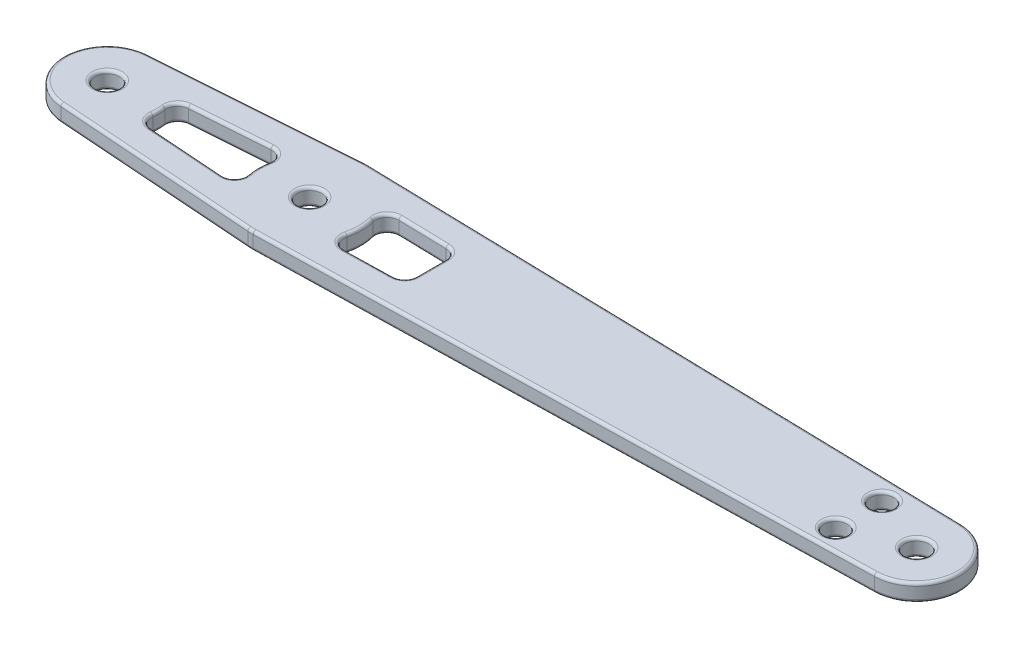
SolidWorks part; units mm, degrees
ref_plane "Front Plane" through (0, 0, 0) normal (0, 0, 1) x (1, 0, 0)
ref_plane "Top Plane" through (0, 0, 0) normal (0, 1, 0) x (1, 0, 0)
ref_plane "Right Plane" through (0, 0, 0) normal (1, 0, 0) x (0, 0, -1)
sketch "Sketch1" plane through (0, 0, 0) normal (0, 1, 0) x (1, 0, 0)
  line L0 (-0.5357, 7.4808) -> (34.2857, 9.9745)
  line L1 (-0.5357, -7.4808) -> (34.2857, -9.9745)
  line L2 (35.2381, 9.9972) -> (140.1786, 7.4979)
  line L3 (140.1786, -7.4979) -> (35.2381, -9.9972)
  circle A0 centre (0, 0) radius 2.1
  circle A1 centre (35, 0) radius 2.1
  circle A2 centre (140, 0) radius 2.1
  arc A3 (-0.5357, 7.4808) -> (-0.5357, -7.4808) centre (0, 0) ccw
  arc A4 (140.1786, -7.4979) -> (140.1786, 7.4979) centre (140, 0) ccw
  arc A5 (35.2381, 9.9972) -> (34.2857, 9.9745) centre (35, 0) ccw
  arc A6 (34.2857, -9.9745) -> (35.2381, -9.9972) centre (35, 0) ccw
  dimension "D1" = 4.2
  dimension "D2" = 4.2
  dimension "D4" = 4.2
  dimension "D6" = 15
  dimension "D7" = 15
  dimension "D8" = 20
  dimension "D3" = 35
  dimension "D5" = 140
extrude "Boss-Extrude1" add sketch "Sketch1" along normal blind 3
sketch "Sketch3" plane through (0, 0, 0) normal (0, -1, 0) x (1, 0, 0)
  line L2 (130.1755, 2.7347) -> (122.0476, 2.9283) construction
  line L3 (35.2381, 9.9972) -> (140.1786, 7.4979) construction
  line L4 (130.1755, -2.7347) -> (122.0476, -2.9283) construction
  line L5 (140.1786, -7.4979) -> (35.2381, -9.9972) construction
  line L6 (120, 0.9288) -> (120, -0.9288) construction
  line L8 (-0.1786, 2.4936) -> (34.6429, 4.9872)
  line L9 (10.782, 3.2785) -> (24.0869, 4.2313)
  line L11 (34.6429, -4.9872) -> (-0.1786, -2.4936)
  line L12 (24.0869, -4.2313) -> (10.782, -3.2785)
  line L22 (35.119, 4.9986) -> (140.0595, 2.4993)
  line L23 (45.6991, 4.7466) -> (54.0476, 4.5478)
  line L24 (56, 2.5483) -> (56, -2.5483)
  line L25 (140.0595, -2.4993) -> (35.119, -4.9986)
  line L26 (54.0476, -4.5478) -> (45.6991, -4.7466)
  arc A0 (26.188, 1.8298) -> (26.188, -1.8298) centre (35, 0) ccw
  arc A1 (8.9385, -1.0502) -> (8.9385, 1.0502) centre (0, 0) ccw
  arc A2 (8.9385, 1.0502) -> (10.782, 3.2785) centre (10.9248, 1.2836) cw
  arc A3 (8.9385, -1.0502) -> (10.782, -3.2785) centre (10.9248, -1.2836) ccw
  arc A4 (26.188, -1.8298) -> (24.0869, -4.2313) centre (24.2297, -2.2364) cw
  arc A5 (26.188, 1.8298) -> (24.0869, 4.2313) centre (24.2297, 2.2364) ccw
  arc A6 (43.7148, -2.2477) -> (43.7148, 2.2477) centre (35, 0) ccw
  circle A7 centre (35, 0) radius 2.1 construction
  arc A8 (43.7148, 2.2477) -> (45.6991, 4.7466) centre (45.6514, 2.7472) cw
  arc A9 (43.7148, -2.2477) -> (45.6991, -4.7466) centre (45.6514, -2.7472) ccw
  arc A10 (56, -2.5483) -> (54.0476, -4.5478) centre (54, -2.5483) cw
  arc A11 (56, 2.5483) -> (54.0476, 4.5478) centre (54, 2.5483) ccw
  arc A13 (131.1365, 1.5615) -> (131.1365, -1.5615) centre (140, 0) ccw construction
  arc A14 (130.1755, -2.7347) -> (131.1365, -1.5615) centre (130.1517, -1.735) ccw construction
  arc A15 (130.1755, 2.7347) -> (131.1365, 1.5615) centre (130.1517, 1.735) cw construction
  arc A16 (122.0476, -2.9283) -> (120, -0.9288) centre (122, -0.9288) cw construction
  arc A17 (122.0476, 2.9283) -> (120, 0.9288) centre (122, 0.9288) ccw construction
  point P55 (120, 0)
  dimension "D1" = 18
  dimension "D2" = 18
  dimension "D5" = 2
  dimension "D6" = 18
  dimension "D10" = 2
  dimension "D11" = 18
  dimension "D13" = 1
  dimension "D15" = 2
  dimension "D9" = 21
  dimension "D12" = 5
  dimension "D14" = 5
  dimension "D16" = 20
  dimension "D3" = 5
  dimension "D4" = 5
  dimension "D7" = 5
  dimension "D8" = 5
extrude "Cut-Extrude1" cut sketch "Sketch3" against normal blind 6
sketch "Sketch5" plane through (0, 0, 0) normal (0, -1, 0) x (1, 0, 0)
  line L0 (140, 0) -> (132.5915, 0) construction
  circle A0 centre (130, 4) radius 2
  circle A1 centre (130, -4) radius 2
  dimension "D1" = 4
  dimension "D2" = 4
  dimension "D3" = 10
extrude "Cut-Extrude2" cut sketch "Sketch5" against normal through all
fillet "Fillet1" radius 0.5 58 edges at (17.4344, 0, -3.7549) (9.3839, 0, -2.5585) (9, 0, 0) (9.3839, 0, 2.5585) (17.4344, 0, 3.7549) (25.735, 0, 3.5533) (26, 0, 0) (26, 3, 0) (25.735, 3, 3.5533) (17.4344, 3, 3.7549) (9.3839, 3, 2.5585) (9, 3, 0) (9.3839, 3, -2.5585) (17.4344, 3, -3.7549) (55.431, 0, -3.9456) (49.8733, 0, -4.6472) (44.0852, 0, -3.9909) (44, 0, 0) (44.0852, 0, 3.9909) (49.8733, 0, 4.6472) (55.431, 0, 3.9456) (55.431, 3, 3.9456) (49.8733, 3, 4.6472) (44.0852, 3, 3.9909) (44, 3, 0) (44.0852, 3, -3.9909) (49.8733, 3, -4.6472) (55.431, 3, -3.9456) (34.7616, 3, 9.9972) (16.875, 3, 8.7277) (-7.5, 3, 0) (16.875, 3, -8.7277) (34.7616, 3, -9.9972) (87.7083, 3, -8.7475) (147.5, 3, 0) (34.7616, 0, 9.9972) (16.875, 0, 8.7277) (-7.5, 0, 0) (16.875, 0, -8.7277) (34.7616, 0, -9.9972) (87.7083, 0, -8.7475) (147.5, 0, 0) (130, 0, -2) (130, 3, -2) (130, 0, 2) (130, 3, 2) (140, 0, 2.1) (140, 3, 2.1) (0, 0, 2.1) (0, 3, 2.1) (25.735, 0, -3.5533) (25.735, 3, -3.5533) (35, 0, 2.1) (35, 3, 2.1) (56, 0, 0) (56, 3, 0) (87.7083, 3, 8.7475) (87.7083, 0, 8.7475)
